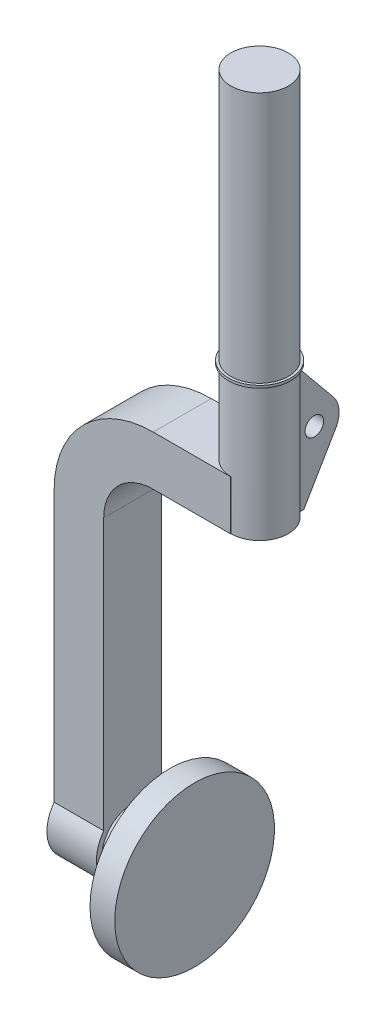
SolidWorks part; units mm, degrees
material "Choose your Material"
ref_plane "Front Plane" through (0, 0, 0) normal (0, 0, 1) x (1, 0, 0)
ref_plane "Top Plane" through (0, 0, 0) normal (0, 1, 0) x (1, 0, 0)
ref_plane "Right Plane" through (0, 0, 0) normal (1, 0, 0) x (0, 0, -1)
sketch "Sketch1" plane through (0, 0, 0) normal (0, 0, 1) x (1, 0, 0)
  line L0 (-114.3, -150.1775) -> (-114.3, 150.1775)
  line L1 (-63.5, 200.9775) -> (15.875, 200.9775)
  line L2 (-165.1, -150.1775) -> (-165.1, 150.1775)
  line L4 (-165.1, -150.1775) -> (-114.3, -150.1775)
  line L5 (15.875, 200.9775) -> (15.875, 251.7775)
  line L6 (-114.3, -150.1775) -> (-114.3, 200.9775) construction
  line L7 (-114.3, 200.9775) -> (15.875, 200.9775) construction
  line L8 (-165.1, -150.1775) -> (-165.1, 251.7775) construction
  line L9 (-165.1, 251.7775) -> (15.875, 251.7775) construction
  line L10 (-18.1686, 281.6613) -> (15.875, 251.7775) construction
  line L11 (-59.6692, 268.3071) -> (-63.5, 251.7775) construction
  line L12 (15.875, 251.7775) -> (-63.5, 251.7775)
  arc A0 (-114.3, 150.1775) -> (-63.5, 200.9775) centre (-63.5, 150.1775) cw
  arc A1 (-165.1, 150.1775) -> (-63.5, 251.7775) centre (-63.5, 150.1775) cw
  arc A2 (-18.1686, 281.6613) -> (-59.6692, 268.3071) centre (-34.925, 262.5725) ccw construction
  circle A3 centre (-34.925, 262.5725) radius 9.525 construction
  point P3 (-114.3, 0)
  point P12 (-114.3, 200.9775)
  dimension "D5" = 101.6
  dimension "D7" = 50.8
  dimension "D9" = 19.05
  dimension "D1" = 114.3
  dimension "D3" = 351.155
  dimension "D6" = 50.8
  dimension "D2" = 10.795
  dimension "D4" = 50.8
extrude "Boss-Extrude1" add sketch "Sketch1" along normal mid plane 59.5312
sketch "Sketch2" plane through (0, -150.1775, 0) normal (0, -1, 0) x (1, 0, 0)
  line L0 (-165.1, 0) -> (-114.3, 0)
  line L1 (-165.1, 29.7656) -> (-165.1, -29.7656) construction
  line L2 (-114.3, 29.7656) -> (-114.3, -29.7656) construction
  line L3 (-165.1, 0) -> (-165.1, 37.207)
  line L4 (-165.1, 37.207) -> (-114.3, 37.207)
  line L5 (-114.3, 37.207) -> (-114.3, 31.75)
  line L6 (-114.3, 31.75) -> (-76.2, 31.75)
  line L7 (-76.2, 31.75) -> (-76.2, 81.915)
  line L8 (-76.2, 81.915) -> (-50.8, 81.915)
  line L9 (-50.8, 81.915) -> (-50.8, 0)
  line L10 (-50.8, 0) -> (-114.3, 0)
  line L11 (-114.3, 29.7656) -> (-114.3, -29.7656) construction
  dimension "D1" = 37.207
  dimension "D2" = 81.915
  dimension "D3" = 25.4
  dimension "D4" = 31.75
  dimension "D5" = 63.5
revolve "Revolve1" add sketch "Sketch2" angle 360 about L0
sketch "Sketch3" plane through (0, 200.9775, 0) normal (0, -1, 0) x (1, 0, 0)
  line L0 (15.875, 29.7656) -> (15.875, -29.7656) construction
  circle A0 centre (15.875, 0) radius 29.464
  dimension "D1" = 58.928
extrude "OleoPist" add sketch "Sketch3" against normal blind 397.764
ref_plane "MaxOleoReachPlane" through (0, 340.6775, 0) normal (0, 1, 0) x (1, 0, 0)
sketch "Sketch5" plane through (0, 340.6775, 0) normal (0, 1, 0) x (1, 0, 0)
  circle A0 centre (15.875, 0) radius 32.004
  circle A1 centre (15.875, 0) radius 29.464 construction
  arc A2 (15.875, -29.464) -> (15.875, 29.464) centre (15.875, 0) ccw construction
  dimension "D1" = 2.54
extrude "RefMaxOleo" add sketch "Sketch5" against normal blind 2.54
sketch "Sketch7" plane through (15.875, -150.1775, 0) normal (1, 0, 0) x (0, 0, -1)
  line L0 (16.764, 488.315) -> (59.8804, 435.8645)
  line L1 (62.1654, 406.8794) -> (29.464, 351.155)
  line L2 (16.764, 351.155) -> (16.764, 488.315)
  line L4 (29.464, 488.315) -> (29.464, 351.155) construction
  line L5 (29.464, 401.955) -> (29.464, 488.315) construction
  line L7 (29.464, 351.155) -> (16.764, 351.155)
  line L11 (-29.464, 351.155) -> (29.464, 351.155) construction
  arc A0 (62.1654, 406.8794) -> (59.8804, 435.8645) centre (40.259, 419.735) ccw
  circle A1 centre (40.259, 419.735) radius 9.525
  point P32 (29.464, 419.735)
  dimension "D1" = 19.05
  dimension "D2" = 25.4
  dimension "D3" = 12.7
  dimension "D4" = 10.795
extrude "Boss-Extrude4" add sketch "Sketch7" along normal mid plane 31.75 contours L0 A0 L1 L7 L2
equation "\"wheelwidth\"= 8"
equation "\"diameter\"= 18.75"
equation "\"D1@Boss-Extrude1\"=\"diameter\"/8"
equation "\"D1@Sketch2\"=\"diameter\"/16*1.25"
equation "\"OleoDia\"=2.32"
equation "\"D1@Sketch3\"=\"OleoDia\""
equation "\"OleoStroke\"=8.66"
equation "\"D1@OleoPist\"=\"OleoStroke\"+7"
equation "\"D2@Sketch2\"=(\"diameter\"/2-\"wheelwidth\"/2)*0.6"
equation "\"D5@Sketch2\"=\"wheelwidth\"/4+0.5"
equation "\"D6@Sketch1\"=\"wheelwidth\"/4"
